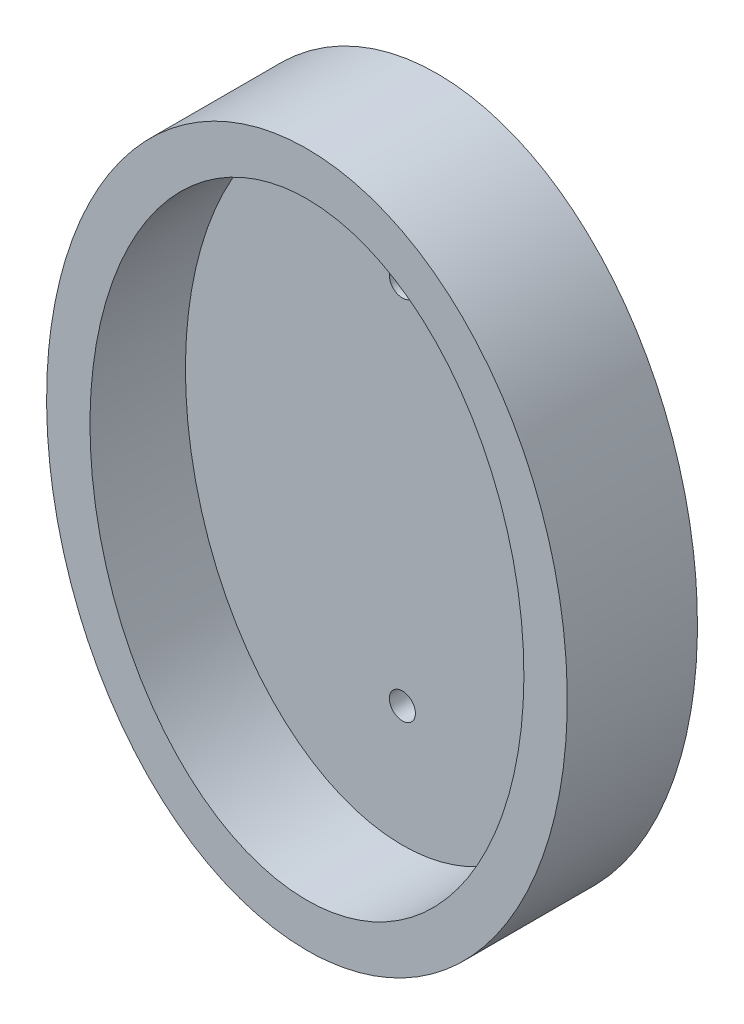
SolidWorks part; units mm, degrees
ref_plane "前视基准面" through (0, 0, 0) normal (0, 0, 1) x (1, 0, 0)
ref_plane "上视基准面" through (0, 0, 0) normal (0, 1, 0) x (1, 0, 0)
ref_plane "右视基准面" through (0, 0, 0) normal (1, 0, 0) x (0, 0, -1)
sketch "草图1" plane through (0, 0, 0) normal (0, 0, 1) x (1, 0, 0)
  line L0 (-61.3435, 0) -> (69.2987, 0) construction
  line L1 (0, 67.4282) -> (0, -66.1315) construction
  ellipse E0 centre (0, 0) end of major axis (0, 35) minor radius 25
  dimension "D1" = 50
  dimension "D2" = 70
extrude "凸台-拉伸1" add sketch "草图1" along normal blind 4
sketch "草图4" plane through (0, 0, 0) normal (0, 0, -1) x (-1, 0, 0)
  line L0 (0, 18.5153) -> (0, -17.6613) construction
  line L1 (-6, 8) -> (6, 8)
  line L2 (-6, 8) -> (-6, -8)
  line L3 (-6, -8) -> (6, -8)
  line L4 (6, 8) -> (6, -8)
  line L5 (-6, 8) -> (6, -8) construction
  line L6 (-6, -8) -> (6, 8) construction
  line L7 (-2.5, 8) -> (-2.5, -8)
  line L8 (2.5, 8) -> (2.5, -8)
  point P0 (0, 0)
  dimension "D1" = 12
  dimension "D2" = 16
  dimension "D3" = 5
extrude "凸台-拉伸3" add sketch "草图4" along normal blind 15 contours L7 L1 L2 L3 | L1 L8 L3 L4
sketch "草图5" plane through (6, 0, 0) normal (1, 0, 0) x (0, 0, -1)
  line L0 (8.2, 8) -> (8.2, -8) construction
  line L1 (15, 8) -> (0, 8) construction
  line L2 (15, -8) -> (0, -8) construction
  line L3 (0, -35) -> (0, 35) construction
  line L4 (15, 0) -> (2.6497, 0) construction
  line L5 (15, 8) -> (15, -8) construction
  circle A0 centre (8.2, 4) radius 1.75
  circle A1 centre (8.2, -4) radius 1.75
  dimension "D2" = 3.5
  dimension "D1" = 8.2
  dimension "D3" = 8
extrude "切除-拉伸2" cut sketch "草图5" against normal blind 15
sketch "草图7" plane through (0, 0, 0) normal (0, 0, -1) x (-1, 0, 0)
  point P0 (0, 0)
  point P1 (-27.7007, 15.268)
sketch "草图8" plane through (0, 0, 0) normal (0, 0, -1) x (-1, 0, 0)
  line L0 (-29.092, 0) -> (65.8878, 0) construction
  circle A0 centre (0, 21.1) radius 1.5
  circle A1 centre (0, -21.1) radius 1.5
  dimension "D1" = 3
  dimension "D2" = 21.1
extrude "切除-拉伸3" cut sketch "草图8" against normal through all
sketch "草图9" plane through (0, 0, 0) normal (0, 0, -1) x (-1, 0, 0)
  ellipse E1 centre (0, 0) end of major axis (0, 35) minor radius 25 construction
  ellipse E2 centre (0, 0) end of major axis (0, 35) minor radius 25
  spline S0 degree 3 poles (-1.1662, -40) (1.1662, -40) (2.3197, -39.9111) (4.0318, -39.65) (4.5995, -39.5416) (5.7288, -39.2823) (6.2923, -39.1309) (9.0701, -38.2747) (11.1503, -37.286) (13.5956, -35.7184) (14.0759, -35.3885) (15.0101, -34.7043) (15.4654, -34.3491) (16.7981, -33.2462) (17.6422, -32.4613) (18.8471, -31.2156) (19.2385, -30.7889) (20.0014, -29.9133) (20.3718, -29.4655) (21.4441, -28.1032) (22.1104, -27.1662) (23.9781, -24.2777) (25.0496, -22.2491) (26.4262, -19.0696) (26.8464, -17.9854) (27.6, -15.8081) (27.9353, -14.7108) (28.8253, -11.3942) (29.2647, -9.1507) (29.7058, -5.7395) (29.8163, -4.5947) (29.927, -2.8659) (29.9546, -2.2868) (29.9912, -1.1319) (30.0002, -0.5556) (29.9992, 2.3211) (29.8523, 4.6059) (29.2659, 9.142) (28.8266, 11.3934) (28.0762, 14.1848) (27.9158, 14.7425) (27.5765, 15.8471) (27.3973, 16.3951) (26.8313, 18.0258) (26.4157, 19.0952) (25.0489, 22.2483) (23.9796, 24.2774) (22.408, 26.7053) (22.081, 27.1865) (21.4076, 28.1291) (21.0609, 28.591) (19.9903, 29.948) (19.2358, 30.8144) (17.6388, 32.4643) (16.7963, 33.2479) (15.4591, 34.3542) (14.9995, 34.7124) (14.0621, 35.3982) (13.585, 35.7254) (12.1283, 36.6586) (11.1232, 37.2166) (9.5609, 37.9507) (9.031, 38.1782) (7.9521, 38.5972) (7.4008, 38.7893) (4.6233, 39.645) (2.3573, 39.9953) (-0.5318, 40.0011) (-1.1147, 39.9802) (-2.2759, 39.8939) (-2.8514, 39.829) (-4.5633, 39.5709) (-5.6851, 39.3148) (-7.3398, 38.8095) (-7.8867, 38.6208) (-8.9712, 38.2031) (-9.5085, 37.9739) (-11.0839, 37.2377) (-12.0932, 36.679) (-14.0373, 35.4376) (-14.9735, 34.7536) (-16.7688, 33.2729) (-17.6147, 32.4875) (-20.0151, 30.0125) (-21.4337, 28.2049) (-23.0109, 25.7753) (-23.3165, 25.2803) (-23.903, 24.2831) (-24.1846, 23.7797) (-24.9961, 22.2561) (-25.4928, 21.2223) (-26.861, 18.0714) (-27.6112, 15.9048) (-28.5132, 12.564) (-28.7767, 11.4323) (-29.224, 9.168) (-29.4089, 8.0326) (-29.8518, 4.6167) (-29.999, 2.3268) (-30.0005, -1.1268) (-29.9641, -2.2835) (-29.8165, -4.5927) (-29.7059, -5.7387) (-29.2646, -9.1513) (-28.8255, -11.3925) (-27.6424, -15.8038) (-26.899, -17.974) (-25.5187, -21.1674) (-25.0182, -22.2116) (-23.9383, -24.245) (-23.3582, -25.2362) (-22.112, -27.164) (-21.4459, -28.1006) (-20.3758, -29.4605) (-20.0073, -29.9063) (-19.2449, -30.7818) (-18.8512, -31.2112) (-16.8393, -33.292) (-15.0755, -34.767) (-12.6426, -36.33) (-12.1434, -36.6289) (-11.1247, -37.194) (-10.6086, -37.4583) (-9.0402, -38.1956) (-7.9677, -38.6135) (-6.3166, -39.1239) (-5.7591, -39.2746) (-4.6294, -39.5355) (-4.0552, -39.6459) (-2.3275, -39.9108) (-1.1662, -40) (1.1662, -40) (2.3197, -39.9111) knots -0.015625 -0.015625 0 0 0.015625 0.015625 0.023437 0.023437 0.03125 0.03125 0.0625 0.0625 0.070312 0.070312 0.078125 0.078125 0.09375 0.09375 0.101562 0.101562 0.109375 0.109375 0.125 0.125 0.15625 0.15625 0.171875 0.171875 0.1875 0.1875 0.21875 0.21875 0.234375 0.234375 0.242187 0.242187 0.25 0.25 0.28125 0.28125 0.3125 0.3125 0.320312 0.320312 0.328125 0.328125 0.34375 0.34375 0.375 0.375 0.382812 0.382812 0.390625 0.390625 0.40625 0.40625 0.421875 0.421875 0.429687 0.429687 0.4375 0.4375 0.453125 0.453125 0.460937 0.460937 0.46875 0.46875 0.5 0.5 0.507812 0.507812 0.515625 0.515625 0.53125 0.53125 0.539062 0.539062 0.546875 0.546875 0.5625 0.5625 0.578125 0.578125 0.59375 0.59375 0.625 0.625 0.632812 0.632812 0.640625 0.640625 0.65625 0.65625 0.6875 0.6875 0.703125 0.703125 0.71875 0.71875 0.75 0.75 0.765625 0.765625 0.78125 0.78125 0.8125 0.8125 0.84375 0.84375 0.859375 0.859375 0.875 0.875 0.890625 0.890625 0.898437 0.898437 0.90625 0.90625 0.9375 0.9375 0.945312 0.945312 0.953125 0.953125 0.96875 0.96875 0.976562 0.976562 0.984375 0.984375 1 1 1.015625 1.015625 1.023438 only from (0, -40) to (0, -40)
  spline S1 degree 3 poles (-1.1662, -40) (1.1662, -40) (2.3197, -39.9111) (4.0318, -39.65) (4.5995, -39.5416) (5.7288, -39.2823) (6.2923, -39.1309) (9.0701, -38.2747) (11.1503, -37.286) (13.5956, -35.7184) (14.0759, -35.3885) (15.0101, -34.7043) (15.4654, -34.3491) (16.7981, -33.2462) (17.6422, -32.4613) (18.8471, -31.2156) (19.2385, -30.7889) (20.0014, -29.9133) (20.3718, -29.4655) (21.4441, -28.1032) (22.1104, -27.1662) (23.9781, -24.2777) (25.0496, -22.2491) (26.4262, -19.0696) (26.8464, -17.9854) (27.6, -15.8081) (27.9353, -14.7108) (28.8253, -11.3942) (29.2647, -9.1507) (29.7058, -5.7395) (29.8163, -4.5947) (29.927, -2.8659) (29.9546, -2.2868) (29.9912, -1.1319) (30.0002, -0.5556) (29.9992, 2.3211) (29.8523, 4.6059) (29.2659, 9.142) (28.8266, 11.3934) (28.0762, 14.1848) (27.9158, 14.7425) (27.5765, 15.8471) (27.3973, 16.3951) (26.8313, 18.0258) (26.4157, 19.0952) (25.0489, 22.2483) (23.9796, 24.2774) (22.408, 26.7053) (22.081, 27.1865) (21.4076, 28.1291) (21.0609, 28.591) (19.9903, 29.948) (19.2358, 30.8144) (17.6388, 32.4643) (16.7963, 33.2479) (15.4591, 34.3542) (14.9995, 34.7124) (14.0621, 35.3982) (13.585, 35.7254) (12.1283, 36.6586) (11.1232, 37.2166) (9.5609, 37.9507) (9.031, 38.1782) (7.9521, 38.5972) (7.4008, 38.7893) (4.6233, 39.645) (2.3573, 39.9953) (-0.5318, 40.0011) (-1.1147, 39.9802) (-2.2759, 39.8939) (-2.8514, 39.829) (-4.5633, 39.5709) (-5.6851, 39.3148) (-7.3398, 38.8095) (-7.8867, 38.6208) (-8.9712, 38.2031) (-9.5085, 37.9739) (-11.0839, 37.2377) (-12.0932, 36.679) (-14.0373, 35.4376) (-14.9735, 34.7536) (-16.7688, 33.2729) (-17.6147, 32.4875) (-20.0151, 30.0125) (-21.4337, 28.2049) (-23.0109, 25.7753) (-23.3165, 25.2803) (-23.903, 24.2831) (-24.1846, 23.7797) (-24.9961, 22.2561) (-25.4928, 21.2223) (-26.861, 18.0714) (-27.6112, 15.9048) (-28.5132, 12.564) (-28.7767, 11.4323) (-29.224, 9.168) (-29.4089, 8.0326) (-29.8518, 4.6167) (-29.999, 2.3268) (-30.0005, -1.1268) (-29.9641, -2.2835) (-29.8165, -4.5927) (-29.7059, -5.7387) (-29.2646, -9.1513) (-28.8255, -11.3925) (-27.6424, -15.8038) (-26.899, -17.974) (-25.5187, -21.1674) (-25.0182, -22.2116) (-23.9383, -24.245) (-23.3582, -25.2362) (-22.112, -27.164) (-21.4459, -28.1006) (-20.3758, -29.4605) (-20.0073, -29.9063) (-19.2449, -30.7818) (-18.8512, -31.2112) (-16.8393, -33.292) (-15.0755, -34.767) (-12.6426, -36.33) (-12.1434, -36.6289) (-11.1247, -37.194) (-10.6086, -37.4583) (-9.0402, -38.1956) (-7.9677, -38.6135) (-6.3166, -39.1239) (-5.7591, -39.2746) (-4.6294, -39.5355) (-4.0552, -39.6459) (-2.3275, -39.9108) (-1.1662, -40) (1.1662, -40) (2.3197, -39.9111) knots -0.015625 -0.015625 0 0 0.015625 0.015625 0.023437 0.023437 0.03125 0.03125 0.0625 0.0625 0.070312 0.070312 0.078125 0.078125 0.09375 0.09375 0.101562 0.101562 0.109375 0.109375 0.125 0.125 0.15625 0.15625 0.171875 0.171875 0.1875 0.1875 0.21875 0.21875 0.234375 0.234375 0.242187 0.242187 0.25 0.25 0.28125 0.28125 0.3125 0.3125 0.320312 0.320312 0.328125 0.328125 0.34375 0.34375 0.375 0.375 0.382812 0.382812 0.390625 0.390625 0.40625 0.40625 0.421875 0.421875 0.429687 0.429687 0.4375 0.4375 0.453125 0.453125 0.460937 0.460937 0.46875 0.46875 0.5 0.5 0.507812 0.507812 0.515625 0.515625 0.53125 0.53125 0.539062 0.539062 0.546875 0.546875 0.5625 0.5625 0.578125 0.578125 0.59375 0.59375 0.625 0.625 0.632812 0.632812 0.640625 0.640625 0.65625 0.65625 0.6875 0.6875 0.703125 0.703125 0.71875 0.71875 0.75 0.75 0.765625 0.765625 0.78125 0.78125 0.8125 0.8125 0.84375 0.84375 0.859375 0.859375 0.875 0.875 0.890625 0.890625 0.898437 0.898437 0.90625 0.90625 0.9375 0.9375 0.945312 0.945312 0.953125 0.953125 0.96875 0.96875 0.976562 0.976562 0.984375 0.984375 1 1 1.015625 1.015625 1.023438 only from (0, -40) to (0, -40)
  dimension "D1" = 5
extrude "凸台-拉伸4" add sketch "草图9" against normal blind 15 contours S1
